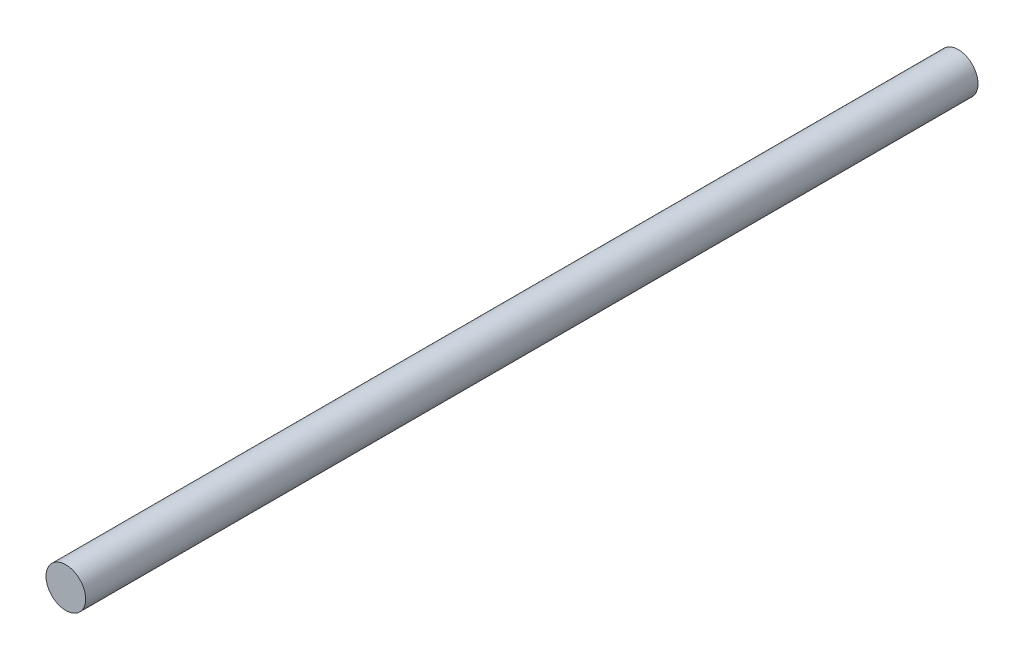
SolidWorks part; units mm, degrees
material "AISI 1020"
ref_plane "Plano frontal" through (0, 0, 0) normal (0, 0, 1) x (1, 0, 0)
ref_plane "Plano superior" through (0, 0, 0) normal (0, 1, 0) x (1, 0, 0)
ref_plane "Plano direito" through (0, 0, 0) normal (1, 0, 0) x (0, 0, -1)
sketch "Esboço1" plane through (0, 0, 0) normal (0, 0, 1) x (1, 0, 0)
  circle A0 centre (0, 0) radius 4
  dimension "D1" = 8
extrude "Ressalto-extrusão1" add sketch "Esboço1" along normal mid plane 180
